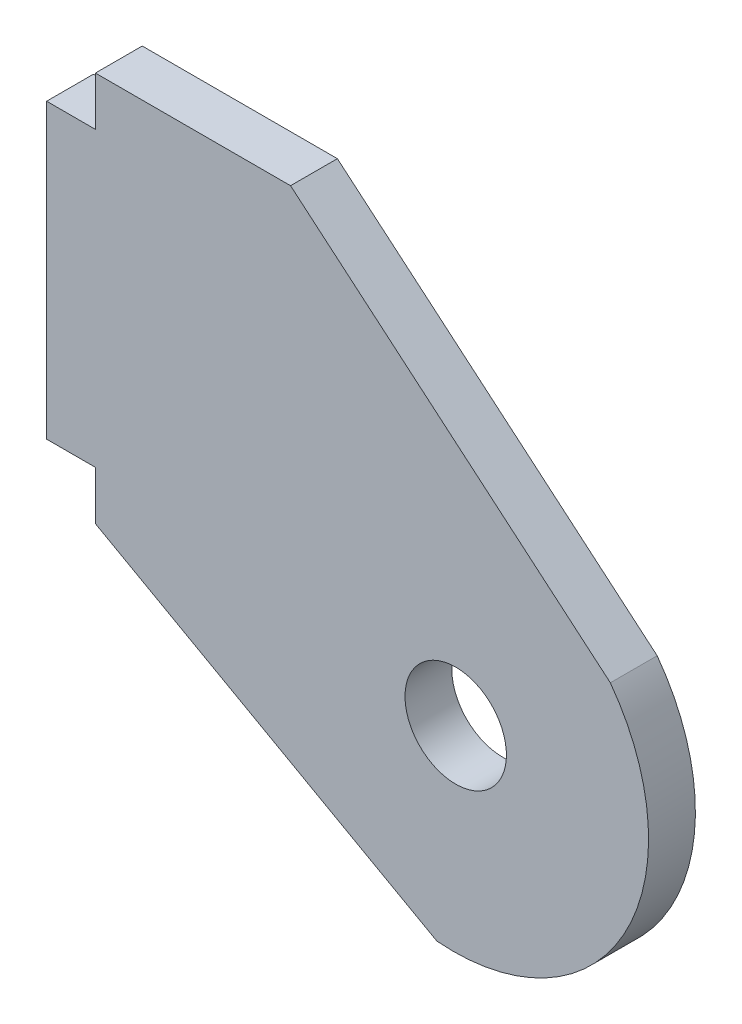
SolidWorks part; units mm, degrees
material "AISI 4130 Steel, normalized at 870C"
ref_plane "X-Y Datum" through (0, 0, 0) normal (0, 0, 1) x (1, 0, 0)
ref_plane "X-Z Datum" through (0, 0, 0) normal (0, 1, 0) x (1, 0, 0)
ref_plane "Y-Z Datum" through (0, 0, 0) normal (1, 0, 0) x (0, 0, -1)
sketch "Sketch1" plane through (0, 0, 0) normal (0, 0, 1) x (1, 0, 0)
  line L0 (427.9194, 0) -> (440.6194, 0)
  line L2 (427.9194, 0) -> (427.9194, -3.175)
  line L9 (427.9194, -25.4) -> (450.1444, -37.8155)
  line L10 (450.1444, -37.8155) -> (461.4322, -17.6092) construction
  line L12 (440.6194, 0) -> (461.4322, -17.6092)
  line L13 (427.9194, -22.225) -> (424.7444, -22.225)
  line L14 (424.7444, -22.225) -> (424.7444, -3.175)
  line L15 (424.7444, -3.175) -> (427.9194, -3.175)
  line L16 (427.9194, -22.225) -> (427.9194, -25.4)
  arc A0 (450.1444, -37.8155) -> (461.4322, -17.6092) centre (451.2216, -25.1613) ccw
  circle A2 centre (451.3682, -25.0582) radius 3.3
  point P11 (0, 0)
  point P12 (0, 0)
  point P15 (447.9946, 21.8143)
  dimension "D2" = 22.225
  dimension "D3" = 12.7
  dimension "D9" = 6.6
  dimension "D10" = 26.6238
  dimension "D1" = 12.7
  dimension "D4" = 3.175
  dimension "D5" = 19.05
  dimension "D6" = 26.4772
  dimension "D7" = 25.4577
  dimension "D8" = 27.2627
extrude "Boss-Extrude1" add sketch "Sketch1" along normal blind 3.048
